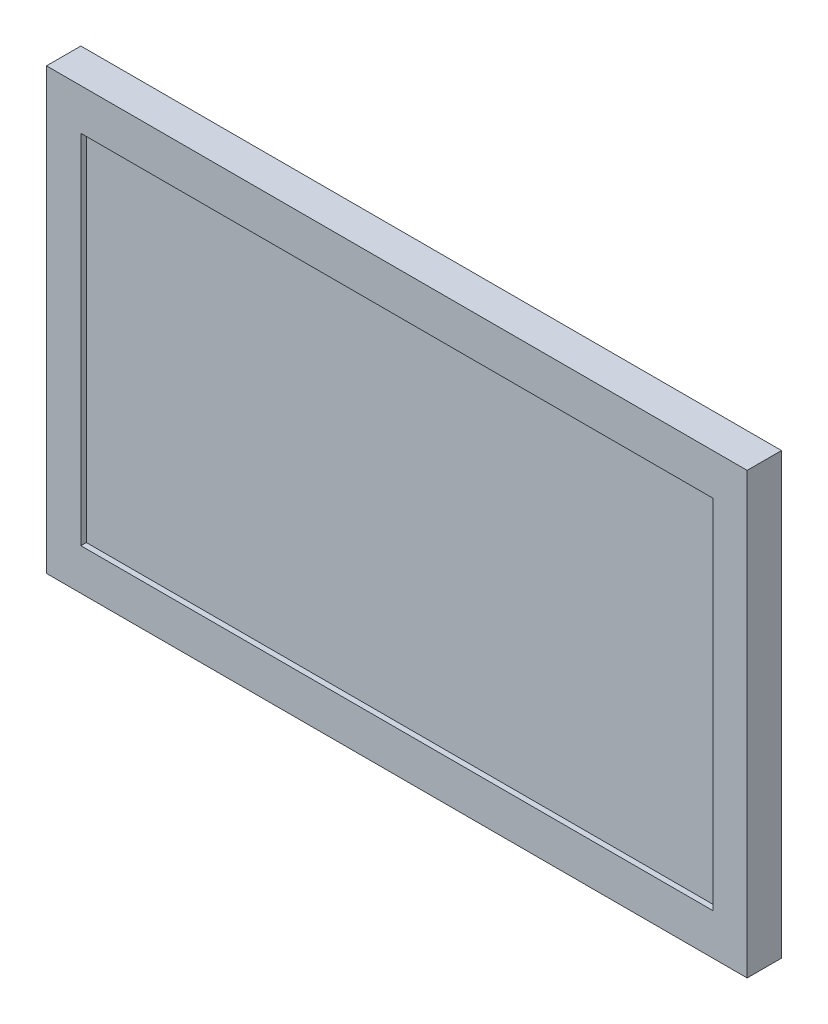
SolidWorks part; units mm, degrees
ref_plane "Front Plane" through (0, 0, 0) normal (0, 0, 1) x (1, 0, 0)
ref_plane "Top Plane" through (0, 0, 0) normal (0, 1, 0) x (1, 0, 0)
ref_plane "Right Plane" through (0, 0, 0) normal (1, 0, 0) x (0, 0, -1)
sketch "Sketch1" plane through (0, 0, 0) normal (0, 0, 1) x (1, 0, 0)
  line L1 (-161.925, -101.6) -> (161.925, -101.6)
  line L2 (-161.925, -101.6) -> (-161.925, 101.6)
  line L3 (-161.925, 101.6) -> (161.925, 101.6)
  line L4 (161.925, -101.6) -> (161.925, 101.6)
  line L5 (-161.925, -101.6) -> (161.925, 101.6) construction
  line L6 (-161.925, 101.6) -> (161.925, -101.6) construction
  point P0 (0, 0)
  dimension "D1" = 323.85
  dimension "D2" = 203.2
extrude "Boss-Extrude1" add sketch "Sketch1" along normal blind 15.875
sketch "Sketch2" plane through (0, 0, 15.875) normal (0, 0, 1) x (1, 0, 0)
  line L1 (-146.05, -82.55) -> (146.05, -82.55)
  line L2 (-146.05, -82.55) -> (-146.05, 82.55)
  line L3 (-146.05, 82.55) -> (146.05, 82.55)
  line L4 (146.05, -82.55) -> (146.05, 82.55)
  line L5 (-146.05, -82.55) -> (146.05, 82.55) construction
  line L6 (-146.05, 82.55) -> (146.05, -82.55) construction
  point P0 (0, 0)
  dimension "D1" = 165.1
  dimension "D2" = 292.1
extrude "Cut-Extrude1" cut sketch "Sketch2" against normal blind 2.54
